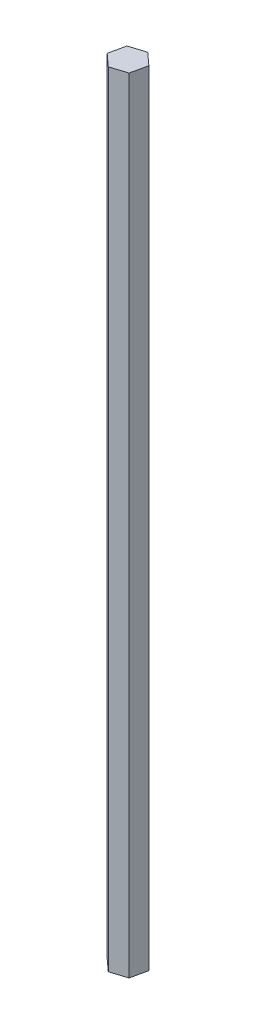
SolidWorks part; units mm, degrees
ref_plane "Front Plane" through (0, 0, 0) normal (0, 0, 1) x (1, 0, 0)
ref_plane "Top Plane" through (0, 0, 0) normal (0, 1, 0) x (1, 0, 0)
ref_plane "Right Plane" through (0, 0, 0) normal (1, 0, 0) x (0, 0, -1)
sketch "Sketch2" plane through (0, 0, 0) normal (0, 1, 0) x (1, 0, 0)
  line L1 (2.1373, -1.9404) -> (2.7491, 0.8807)
  line L2 (2.7491, 0.8807) -> (0.6118, 2.8212)
  line L3 (0.6118, 2.8212) -> (-2.1373, 1.9404)
  line L4 (-2.1373, 1.9404) -> (-2.7491, -0.8807)
  line L5 (-2.7491, -0.8807) -> (-0.6118, -2.8212)
  line L6 (-0.6118, -2.8212) -> (2.1373, -1.9404)
  circle A0 centre (0, 0) radius 2.5 construction
extrude "Boss-Extrude1" add sketch "Sketch2" along normal blind 136.525
